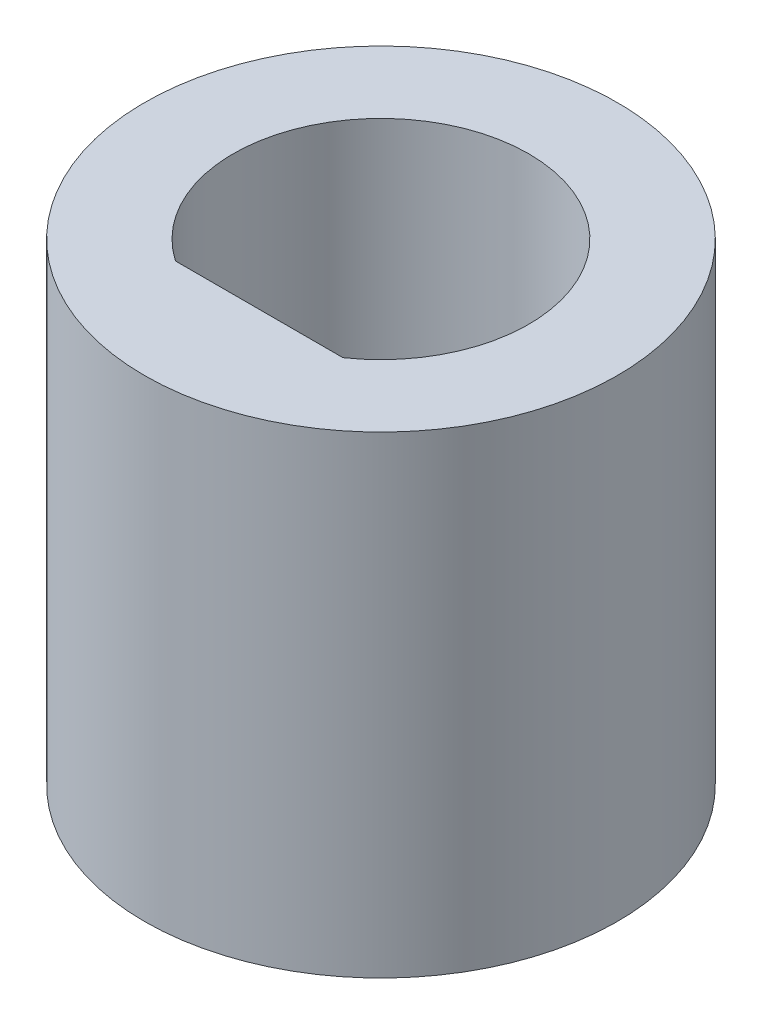
SolidWorks part; units mm, degrees
ref_plane "Front Plane" through (0, 0, 0) normal (0, 0, 1) x (1, 0, 0)
ref_plane "Top Plane" through (0, 0, 0) normal (0, 1, 0) x (1, 0, 0)
ref_plane "Right Plane" through (0, 0, 0) normal (1, 0, 0) x (0, 0, -1)
sketch "Sketch1" plane through (0, 0, 0) normal (0, 1, 0) x (1, 0, 0)
  line L0 (-1.7706, -2.575) -> (1.7706, -2.575)
  circle A0 centre (0, 0) radius 3.125 construction
  arc A1 (-1.7706, -2.575) -> (1.7706, -2.575) centre (0, 0) cw
  circle A2 centre (0, 0) radius 5
  point P5 (0, 3.125)
  dimension "D1" = 6.25
  dimension "D3" = 10
  dimension "D2" = 5.7
extrude "Boss-Extrude1" add sketch "Sketch1" along normal blind 10
